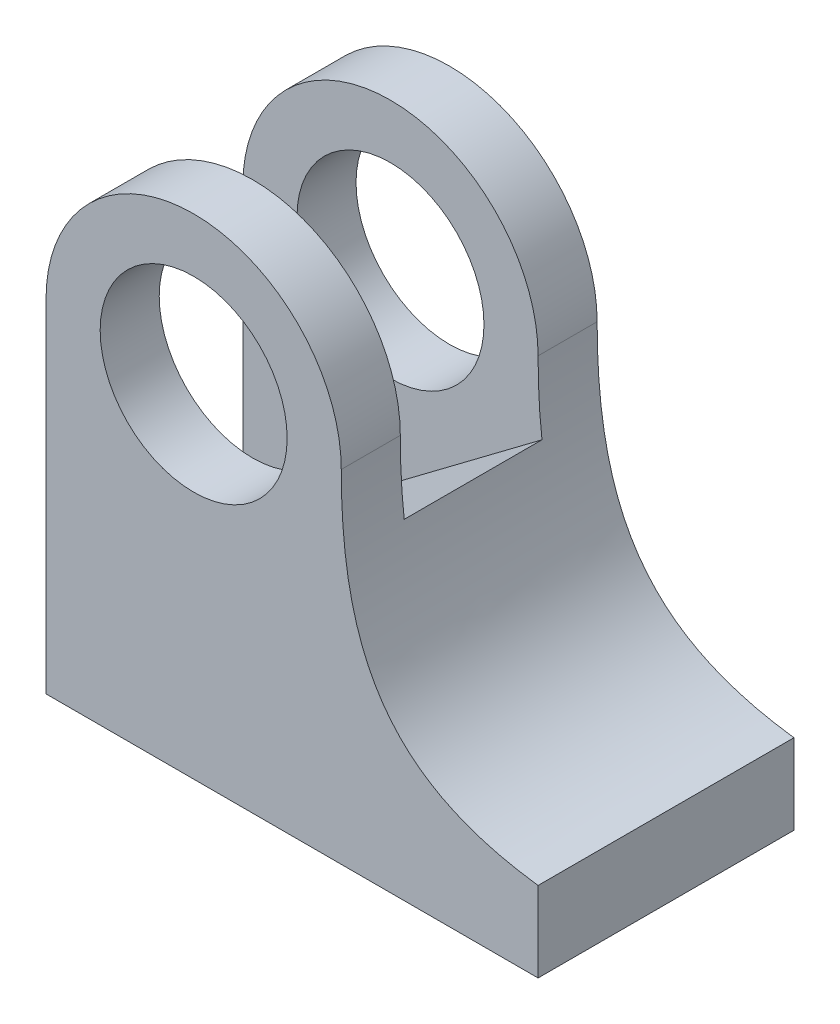
SolidWorks part; units mm, degrees
ref_plane "Front Plane" through (0, 0, 0) normal (0, 0, 1) x (1, 0, 0)
ref_plane "Top Plane" through (0, 0, 0) normal (0, 1, 0) x (1, 0, 0)
ref_plane "Right Plane" through (0, 0, 0) normal (1, 0, 0) x (0, 0, -1)
sketch "Sketch1" plane through (0, 0, 0) normal (0, 0, 1) x (1, 0, 0)
  line L0 (-15, 0) -> (-15, -34.7538)
  line L1 (-15, -34.7538) -> (35, -34.7538)
  line L2 (35, -34.7538) -> (35, -26.6074)
  circle A0 centre (0, 0) radius 9.5
  arc A2 (15, 0) -> (-15, 0) centre (0, 0) ccw
  spline S0 degree 3 poles (35, -26.6074) (19.6218, -24.6218) (15, -15.8296) (15, 0) knots 0 0 0 0 1 1 1 1
extrude "Boss-Extrude1" add sketch "Sketch1" along normal blind 26
ref_plane "Plane1" through (9.5846, 7.2045, 0) normal (-0.7994, -0.6009, 0) x (0, 0, 1)
ref_plane "Plane3" through (17.5782, 13.213, 0) normal (0.7994, 0.6009, 0) x (0, 0, -1)
ref_plane "Plane4" through (15, 0, 0) normal (1, 0, 0) x (0, 0, -1)
sketch "Sketch5" plane through (17.5782, 13.213, 0) normal (0.7994, 0.6009, 0) x (0, 0, -1)
  line L18 (-20, 15) -> (-6, 15)
  line L19 (0, 15) -> (-26, 15) construction
  line L20 (-20, -15) -> (-6, -15)
  line L21 (-6, 15) -> (-6, -15)
  line L22 (-20, 15) -> (-20, -15)
  point P8 (-13, 0)
  point P13 (-13, 15)
extrude "Cut-Extrude2" cut sketch "Sketch5" against normal blind 57
